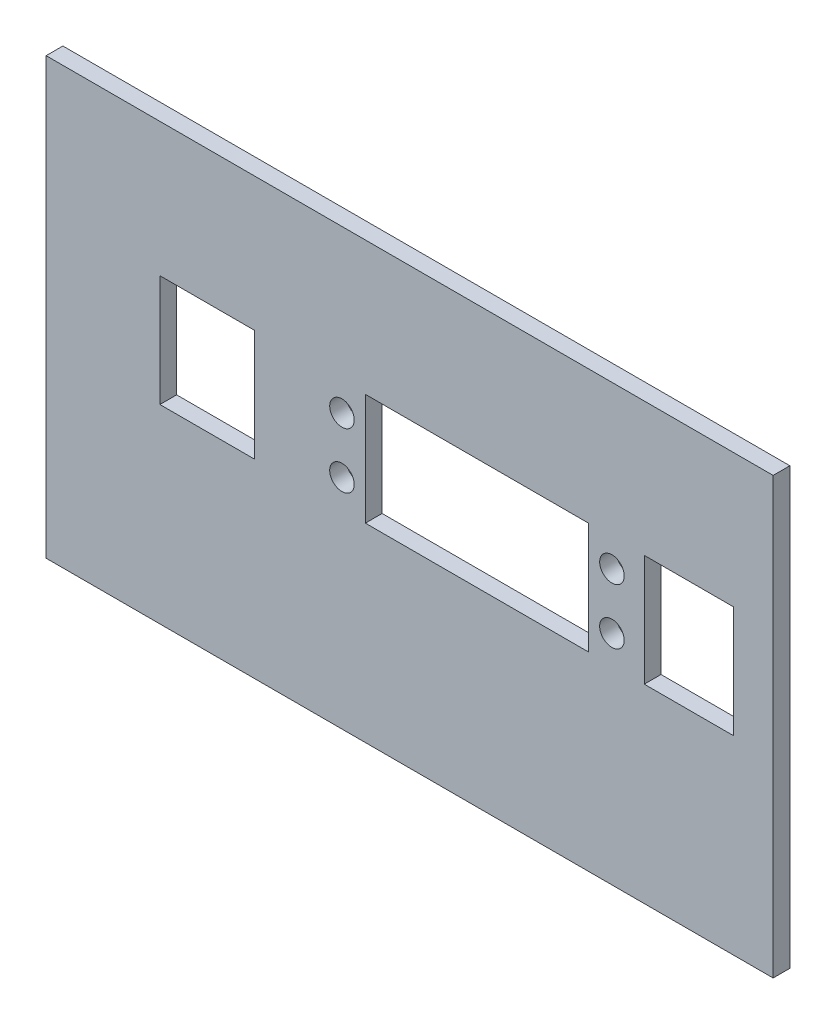
SolidWorks part; units mm, degrees
ref_plane "前视基准面" through (0, 0, 0) normal (0, 0, 1) x (1, 0, 0)
ref_plane "上视基准面" through (0, 0, 0) normal (0, 1, 0) x (1, 0, 0)
ref_plane "右视基准面" through (0, 0, 0) normal (1, 0, 0) x (0, 0, -1)
sketch "草图1" plane through (0, 0, 0) normal (0, 0, 1) x (1, 0, 0)
  line L0 (18.8415, 8.7222) -> (18.8415, -11.2778)
  line L1 (-38.3963, 32.6887) -> (91.9436, 32.6887)
  line L2 (-38.3963, 32.6887) -> (-38.3963, -45.3491)
  line L3 (-38.3963, -45.3491) -> (91.9436, -45.3491)
  line L4 (91.9436, 32.6887) -> (91.9436, -45.3491)
  line L5 (58.8415, 8.7222) -> (58.8415, -11.2778)
  line L6 (18.8415, 8.7222) -> (58.8415, 8.7222)
  line L7 (18.8415, -11.2778) -> (58.8415, -11.2778)
  line L9 (-0.9995, 8.7222) -> (-17.9995, 8.7222)
  line L10 (-0.9995, 8.7222) -> (-0.9995, -11.2778)
  line L11 (-0.9995, -11.2778) -> (-17.9995, -11.2778)
  line L12 (-17.9995, 8.7222) -> (-17.9995, -11.2778)
  line L13 (68.8415, -11.2778) -> (84.8415, -11.2778)
  line L14 (68.8415, -11.2778) -> (68.8415, 8.7222)
  line L15 (68.8415, 8.7222) -> (84.8415, 8.7222)
  line L16 (84.8415, -11.2778) -> (84.8415, 8.7222)
  circle A3 centre (14.6415, 3.7222) radius 2.2
  circle A4 centre (14.6415, -6.2778) radius 2.2
  circle A5 centre (63.0415, 3.7222) radius 2.2
  circle A6 centre (63.0415, -6.2778) radius 2.2
  dimension "D3" = 10
  dimension "D2" = 17
  dimension "D4" = 16
  dimension "D5" = 48.4
  dimension "D6" = 48.4
  dimension "D10" = 40
extrude "凸台-拉伸1" add sketch "草图1" along normal mid plane 3
sketch "草图2" plane through (0, 0, 1.5) normal (0, 0, 1) x (1, 0, 0)
  line L0 (-38.3963, -45.3491) -> (81.6037, -45.3491)
  line L1 (-38.3963, -45.3491) -> (91.9436, -45.3491) construction
  line L2 (81.6037, -45.3491) -> (81.6037, -42.3491)
  line L3 (81.6037, -42.3491) -> (-38.3963, -42.3491)
  line L4 (-38.3963, 32.6887) -> (-38.3963, -45.3491) construction
  line L5 (-38.3963, -42.3491) -> (-38.3963, -45.3491)
  dimension "D1" = 120
  dimension "D2" = 3
extrude "凸台-拉伸2" add sketch "草图2" against normal blind 9
sketch "草图3" plane through (0, -42.3491, 0) normal (0, 1, 0) x (1, 0, 0)
  line L0 (-38.3963, 7.5) -> (-38.3963, 1.5) construction
  circle A0 centre (-31.3963, 4.5) radius 2
  circle A1 centre (74.6037, 4.5) radius 2
  point P6 (-38.3963, 4.5)
  dimension "D1" = 7
  dimension "D2" = 113
extrude "切除-拉伸1" cut sketch "草图3" against normal blind 6
